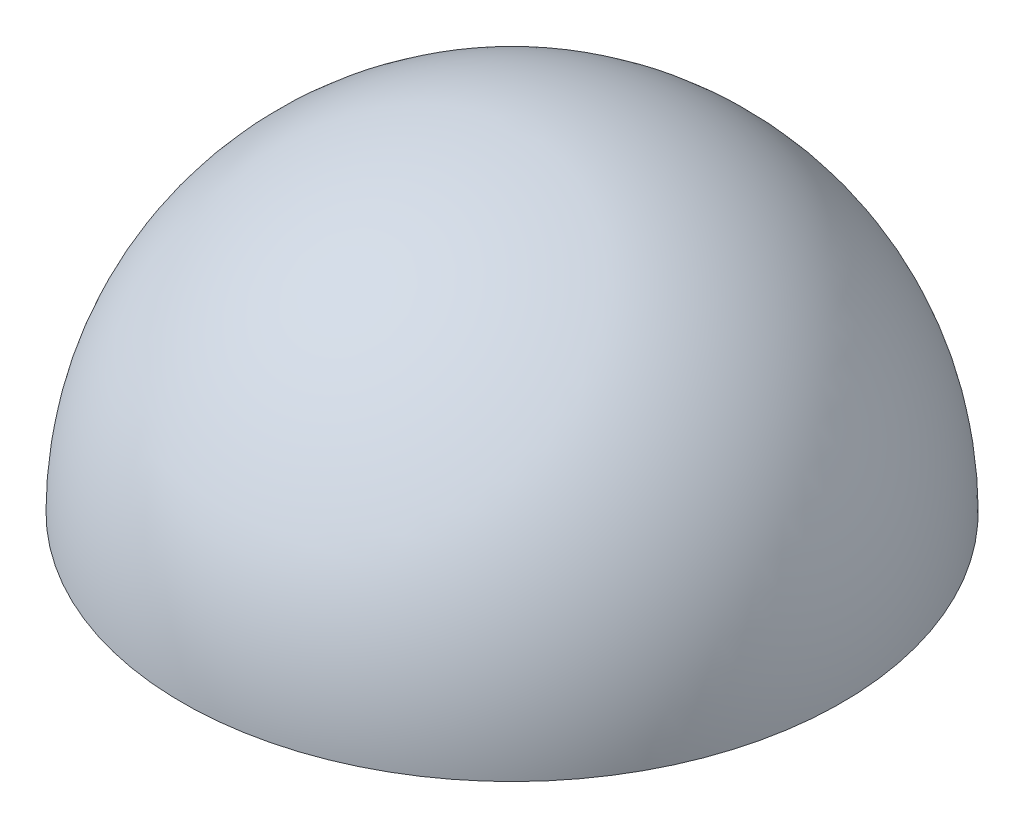
SolidWorks part; units mm, degrees
ref_plane "Front" through (0, 0, 0) normal (0, 0, 1) x (1, 0, 0)
ref_plane "Top" through (0, 0, 0) normal (0, 1, 0) x (1, 0, 0)
ref_plane "Right" through (0, 0, 0) normal (1, 0, 0) x (0, 0, -1)
sketch "Sketch1" plane through (0, 0, 0) normal (0, 1, 0) x (1, 0, 0)
  line L0 (-50.8, 0) -> (50.8, 0)
  arc A0 (50.8, 0) -> (-50.8, 0) centre (0, 0) ccw
revolve "Revolve1" add sketch "Sketch1" angle 180 about L0
